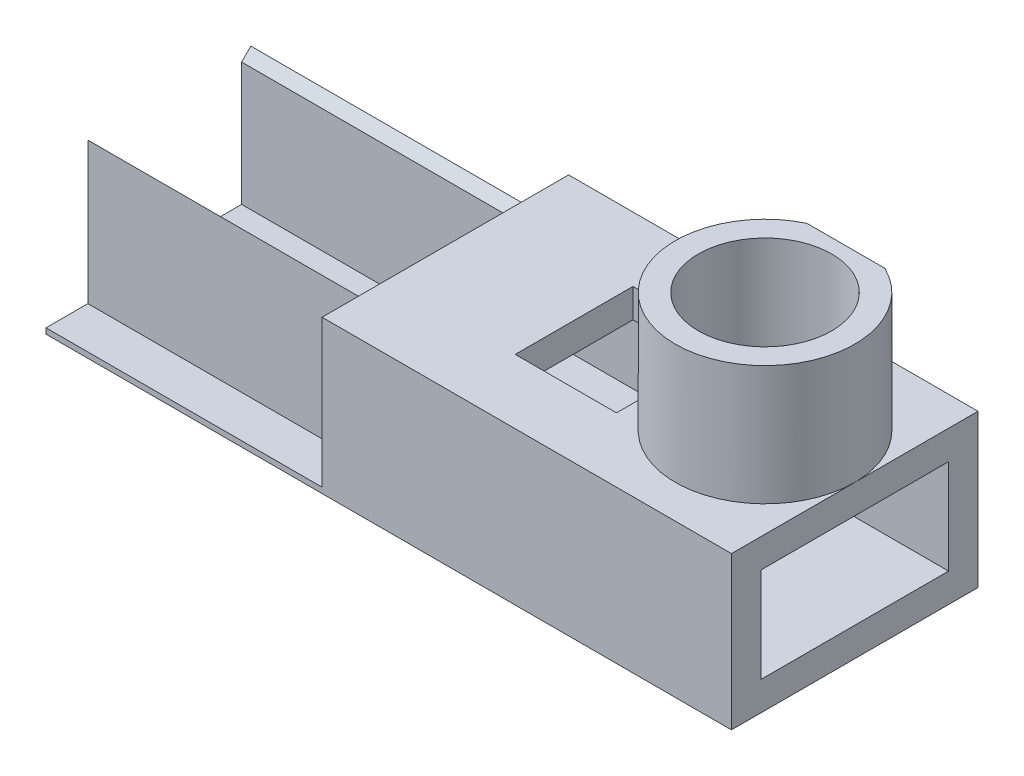
SolidWorks part; units mm, degrees
ref_plane "Front Plane" through (0, 0, 0) normal (0, 0, 1) x (1, 0, 0)
ref_plane "Top Plane" through (0, 0, 0) normal (0, 1, 0) x (1, 0, 0)
ref_plane "Right Plane" through (0, 0, 0) normal (1, 0, 0) x (0, 0, -1)
sketch "Sketch2" plane through (0, 0, 0) normal (1, 0, 0) x (0, 0, -1)
  line L1 (-1.3885, 10.7458) -> (19.4115, 10.7458)
  line L2 (-1.3885, 10.7458) -> (-1.3885, 0.1458)
  line L3 (-1.3885, 0.1458) -> (19.4115, 0.1458)
  line L4 (19.4115, 10.7458) -> (19.4115, 0.1458)
  line L9 (-4.3885, 13.7458) -> (22.4115, 13.7458)
  line L10 (-4.3885, 13.7458) -> (-4.3885, -2.8542)
  line L11 (-4.3885, -2.8542) -> (22.4115, -2.8542)
  line L12 (22.4115, 13.7458) -> (22.4115, -2.8542)
  dimension "D1" = 20.8
  dimension "D2" = 10.6
  dimension "D3" = 3
  dimension "D4" = 3
  dimension "D5" = 3
  dimension "D6" = 3
extrude "Boss-Extrude3" add sketch "Sketch2" along normal blind 19.5 contours L10 L9 L12 L11 | L2 L1 L4 L3
sketch "Sketch8" plane through (0, 13.7458, 0) normal (0, 1, 0) x (1, 0, 0)
  line L0 (0, 22.4115) -> (19.5, -4.3885) construction
  circle A0 centre (9.75, 9.0115) radius 7.25
  circle A1 centre (9.75, 9.0115) radius 9.75
  dimension "D1" = 14.5
  dimension "D2" = 19.5
extrude "Boss-Extrude5" add sketch "Sketch8" along normal blind 13.0105
sketch "Sketch9" plane through (0, 13.7458, 0) normal (0, 1, 0) x (1, 0, 0)
  line L0 (0, 22.4115) -> (19.5, -4.3885) construction
  circle A0 centre (9.75, 9.0115) radius 7.25
extrude "Cut-Extrude1" cut sketch "Sketch9" against normal blind 5
sketch "Sketch11" plane through (0, 0, 0) normal (-1, 0, 0) x (0, 0, 1)
  line L1 (-19.4115, 10.7458) -> (1.3885, 10.7458)
  line L2 (-19.4115, 10.7458) -> (-19.4115, 0.1458)
  line L3 (-19.4115, 0.1458) -> (1.3885, 0.1458)
  line L4 (1.3885, 10.7458) -> (1.3885, 0.1458)
  line L5 (-19.2115, 10.5958) -> (1.1885, 10.5958)
  line L6 (-19.2115, 10.5958) -> (-19.2115, 0.2958)
  line L7 (-19.2115, 0.2958) -> (1.1885, 0.2958)
  line L8 (1.1885, 10.5958) -> (1.1885, 0.2958)
  dimension "D1" = 0.2
  dimension "D2" = 0.2
  dimension "D3" = 0.15
  dimension "D4" = 0.15
extrude "Boss-Extrude7" add sketch "Sketch11" against normal blind 19.5
sketch "Sketch12" plane through (0, 13.7458, 0) normal (0, 1, 0) x (1, 0, 0)
  line L0 (0, 22.4115) -> (19.5, -4.3885) construction
  circle A0 centre (9.75, 9.0115) radius 7.2483
extrude "Cut-Extrude3" cut sketch "Sketch12" against normal blind 4
sketch "Sketch14" plane through (0, 0, 0) normal (-1, 0, 0) x (0, 0, 1)
  line L1 (-22.4115, 13.7458) -> (4.3885, 13.7458)
  line L2 (-22.4115, 13.7458) -> (-22.4115, -2.8542)
  line L3 (-22.4115, -2.8542) -> (4.3885, -2.8542)
  line L4 (4.3885, 13.7458) -> (4.3885, -2.8542)
  line L5 (-19.2115, 10.5958) -> (1.1885, 10.5958)
  line L6 (-19.2115, 10.5958) -> (-19.2115, 0.2958)
  line L7 (-19.2115, 0.2958) -> (1.1885, 0.2958)
  line L8 (1.1885, 10.5958) -> (1.1885, 0.2958)
extrude "Boss-Extrude8" add sketch "Sketch14" along normal blind 24
sketch "Sketch15" plane through (0, -2.8542, 0) normal (0, -1, 0) x (1, 0, 0)
  line L0 (19.5, -22.4115) -> (-24, -22.4115) construction
  circle A0 centre (-1.2425, -9.0115) radius 8
  dimension "D1" = 16
  dimension "D2" = 13.4
extrude "Cut-Extrude5" cut sketch "Sketch15" against normal blind 5
sketch "Sketch16" plane through (0, 13.7458, 0) normal (0, 1, 0) x (1, 0, 0)
  line L0 (19.5, 22.4115) -> (-24, 22.4115) construction
  line L1 (0, 15.4115) -> (-11.0041, 15.4115)
  line L2 (0, 15.4115) -> (0, 2.6115)
  line L3 (0, 2.6115) -> (-11.0041, 2.6115)
  line L4 (-11.0041, 15.4115) -> (-11.0041, 2.6115)
  line L5 (19.5, -4.3885) -> (-24, -4.3885) construction
  dimension "D1" = 7
  dimension "D2" = 7
extrude "Cut-Extrude6" cut sketch "Sketch16" against normal blind 5
chamfer "Chamfer4" distance 2 angle 45 1 edges at (-1.2425, 0.2958, -17.0115)
sketch "Sketch17" plane through (-24, 0, 0) normal (-1, 0, 0) x (0, 0, 1)
  line L1 (-22.4115, 13.7458) -> (4.3885, 13.7458)
  line L2 (-22.4115, 13.7458) -> (-22.4115, -2.8542)
  line L3 (-22.4115, -2.8542) -> (4.3885, -2.8542)
  line L4 (4.3885, 13.7458) -> (4.3885, -2.8542)
extrude "Boss-Extrude9" add sketch "Sketch17" along normal blind 1
sketch "Sketch18" plane through (-25, 0, 0) normal (-1, 0, 0) x (0, 0, 1)
  line L0 (-22.4115, 13.7458) -> (4.3885, -2.8542) construction
  circle A0 centre (-9.0115, 5.4458) radius 4
  dimension "D1" = 8
extrude "Cut-Extrude7" cut sketch "Sketch18" against normal blind 1
sketch "Sketch19" plane through (-25, 0, 0) normal (-1, 0, 0) x (0, 0, 1)
  line L0 (-16.8615, 12.1458) -> (-17.8615, 13.1458)
  line L1 (-16.8615, 12.1458) -> (-1.1615, 12.1458)
  line L2 (-16.8615, 12.1458) -> (-16.8615, -1.2542)
  line L3 (-16.8615, -1.2542) -> (-1.1615, -1.2542)
  line L4 (-1.1615, 12.1458) -> (-1.1615, -1.2542)
  line L5 (-22.4115, 13.7458) -> (-22.4115, -2.8542) construction
  line L6 (-1.1615, 12.1458) -> (-0.1615, 13.1458)
  line L8 (4.3885, 13.7458) -> (-22.4115, 13.7458) construction
  line L11 (-17.8615, 13.1458) -> (-0.1615, 13.1458)
  line L12 (-17.8615, 13.1458) -> (-17.8615, -2.2542)
  line L13 (-17.8615, -2.2542) -> (-0.1615, -2.2542)
  line L14 (-0.1615, 13.1458) -> (-0.1615, -2.2542)
  dimension "D1" = 15.7
  dimension "D2" = 5.55
  dimension "D3" = 13.4
  dimension "D4" = 1.6
  dimension "D5" = 1
  dimension "D6" = 1
  dimension "D7" = 1
  dimension "D8" = 1
extrude "Boss-Extrude11" add sketch "Sketch19" along normal blind 30 contours L14 L6 L4 L3 L2 L0 L12 L13
sketch "Sketch20" plane through (0, -2.2542, 0) normal (0, -1, 0) x (1, 0, 0)
  line L1 (-25, 4.3885) -> (-55.0113, 4.3885)
  line L2 (-25, 4.3885) -> (-25, -22.4115)
  line L3 (-25, -22.4115) -> (-55.0113, -22.4115)
  line L4 (-55.0113, 4.3885) -> (-55.0113, -22.4115)
  line L5 (19.5, -22.4115) -> (-25, -22.4115) construction
  dimension "D1" = 30.0113
  dimension "D2" = 0
extrude "Boss-Extrude12" add sketch "Sketch20" along normal blind 0.6
sketch "Sketch23" plane through (-24, 0, 0) normal (1, 0, 0) x (0, 0, -1)
  circle A0 centre (9.0115, 5.4458) radius 6.7032
extrude "Cut-Extrude9" cut sketch "Sketch23" along normal blind 5
sketch "Sketch25" plane through (0, 26.7563, 0) normal (0, 1, 0) x (1, 0, 0)
  line L1 (0, 20.2424) -> (20.8401, 20.2424)
  line L2 (0, 20.2424) -> (0, 17.7942)
  line L3 (0, 17.7942) -> (20.8401, 17.7942)
  line L4 (20.8401, 20.2424) -> (20.8401, 17.7942)
extrude "Cut-Extrude10" cut sketch "Sketch25" against normal blind 13.01
